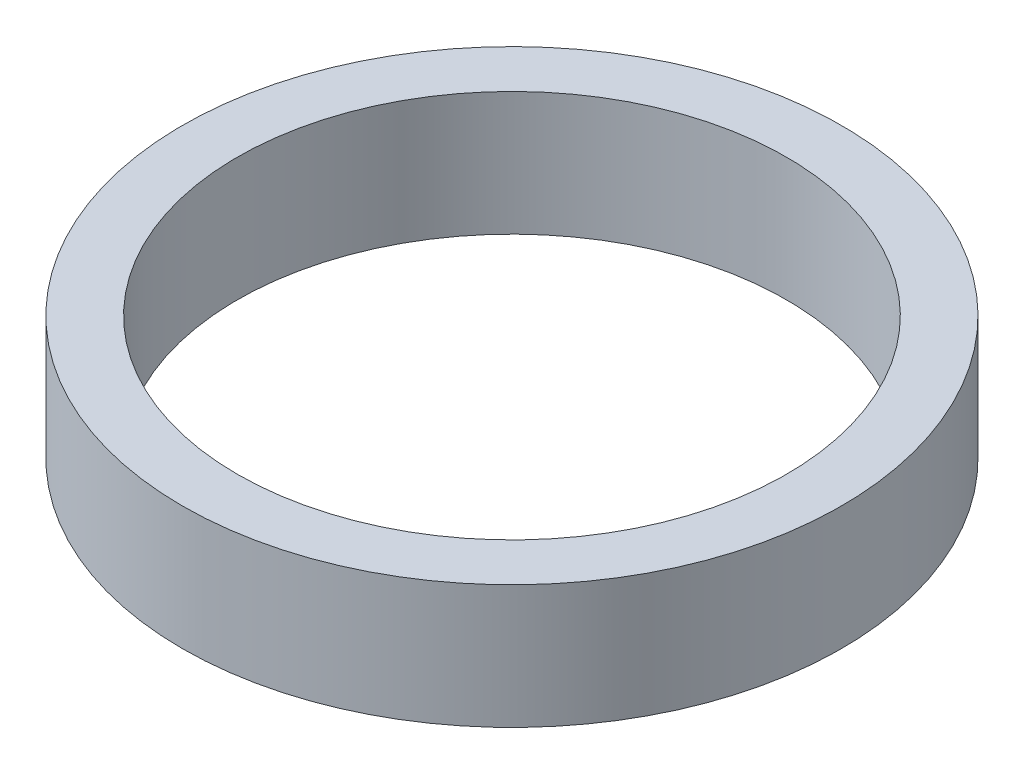
SolidWorks part; units mm, degrees
ref_plane "前视基准面" through (0, 0, 0) normal (0, 0, 1) x (1, 0, 0)
ref_plane "上视基准面" through (0, 0, 0) normal (0, 1, 0) x (1, 0, 0)
ref_plane "右视基准面" through (0, 0, 0) normal (1, 0, 0) x (0, 0, -1)
sketch "草图1" plane through (0, 0, 0) normal (0, 1, 0) x (1, 0, 0)
  circle A0 centre (0, 0) radius 20
  circle A1 centre (0, 0) radius 24
extrude "凸台-拉伸2" add sketch "草图1" along normal blind 9
